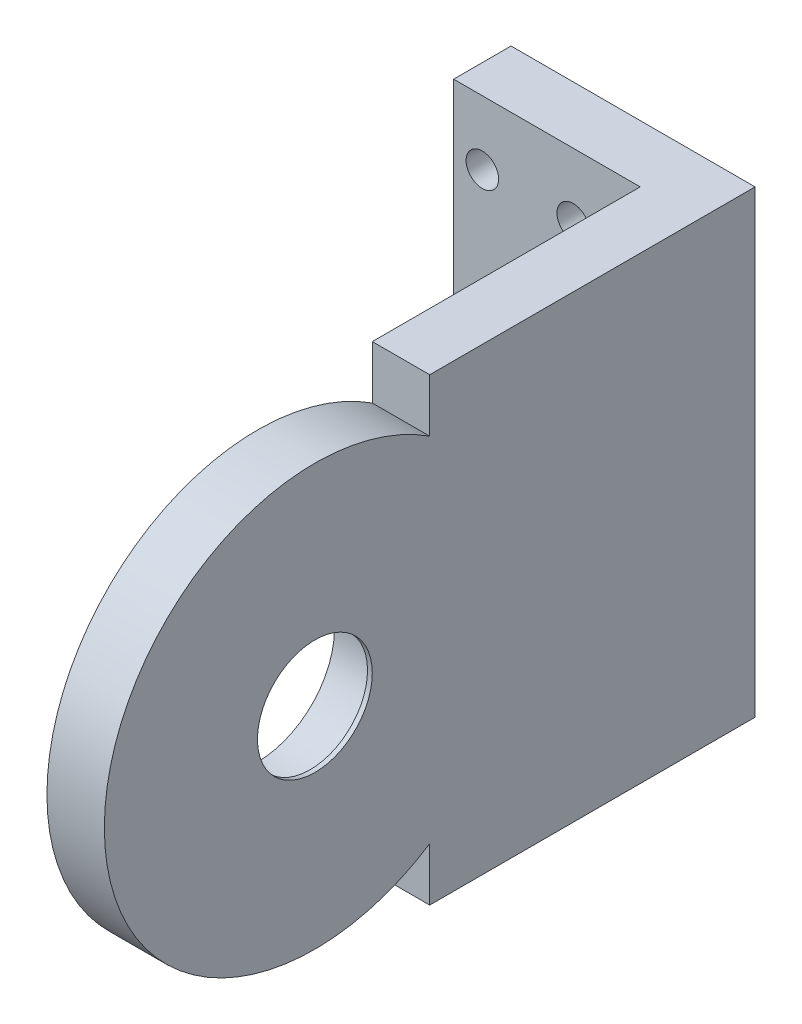
SolidWorks part; units mm, degrees
ref_plane "Front Plane" through (0, 0, 0) normal (0, 0, 1) x (1, 0, 0)
ref_plane "Top Plane" through (0, 0, 0) normal (0, 1, 0) x (1, 0, 0)
ref_plane "Right Plane" through (0, 0, 0) normal (1, 0, 0) x (0, 0, -1)
ref_plane "Plane1" through (336.5, 0, 0) normal (1, 0, 0) x (0, 0, -1)
sketch "Sketch1" plane through (336.5, 0, 0) normal (1, 0, 0) x (0, 0, -1)
  circle A0 centre (-300, 300) radius 22
extrude "Boss-Extrude1" add sketch "Sketch1" along normal blind 6
sketch "Sketch2" plane through (336.5, 0, 0) normal (1, 0, 0) x (0, 0, -1)
  line L0 (-254, 276) -> (-288, 276)
  line L1 (-288, 276) -> (-288, 324)
  line L2 (-288, 324) -> (-254, 324)
  line L3 (-254, 324) -> (-254, 276)
extrude "Boss-Extrude2" add sketch "Sketch2" along normal blind 6
sketch "Sketch3" plane through (336.5, 0, 0) normal (1, 0, 0) x (0, 0, -1)
  circle A0 centre (-300, 300) radius 6
extrude "Cut-Extrude1" cut sketch "Sketch3" along normal blind 6
sketch "Sketch4" plane through (336.5, 0, 0) normal (1, 0, 0) x (0, 0, -1)
  circle A0 centre (-300, 300) radius 8.05
extrude "Cut-Extrude2" cut sketch "Sketch4" along normal blind 5.5
ref_plane "Plane2" through (0, 0, 254) normal (0, 0, 1) x (1, 0, 0)
sketch "Sketch5" plane through (0, 0, 254) normal (0, 0, 1) x (1, 0, 0)
  line L0 (317, 276) -> (336.51, 276)
  line L1 (336.51, 276) -> (336.51, 324)
  line L2 (336.51, 324) -> (317, 324)
  line L3 (317, 324) -> (317, 276)
  circle A0 centre (320, 282.7) radius 1.7
  circle A1 centre (320, 317.3) radius 1.7
  circle A2 centre (329.5, 282.7) radius 1.7
  circle A3 centre (329.5, 317.3) radius 1.7
extrude "Boss-Extrude3" add sketch "Sketch5" along normal blind 6
